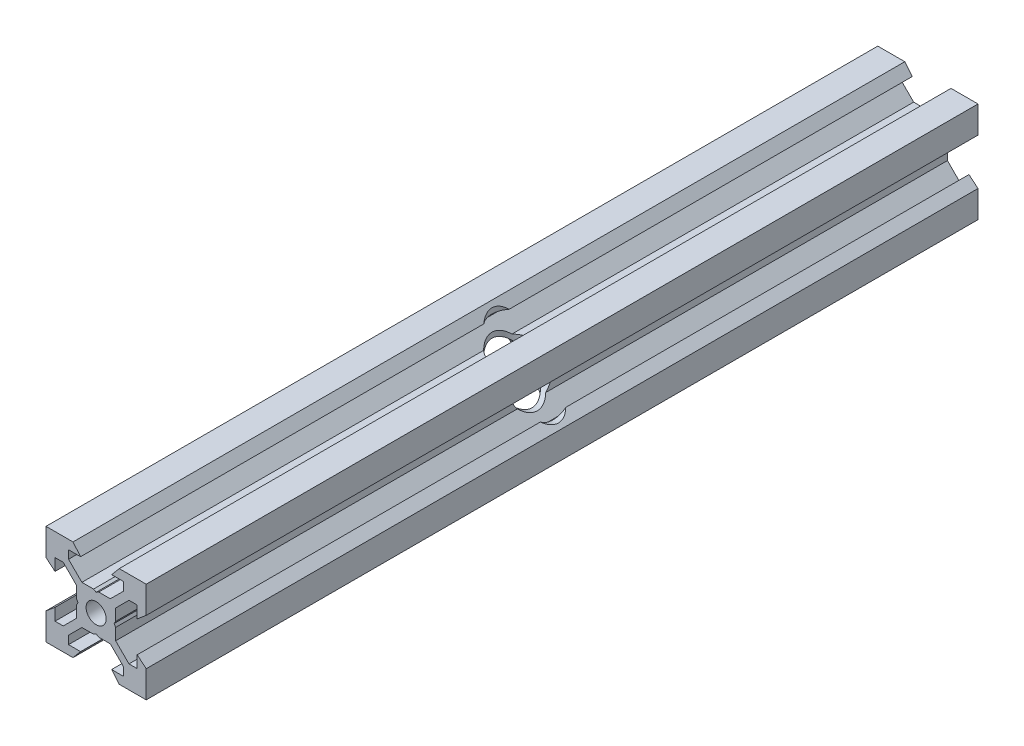
SolidWorks part; units mm, degrees
material "3.3535 (EN-AW 5754)"
ref_plane "Front Plane" through (0, 0, 0) normal (0, 0, 1) x (1, 0, 0)
ref_plane "Top Plane" through (0, 0, 0) normal (0, 1, 0) x (1, 0, 0)
ref_plane "Right Plane" through (0, 0, 0) normal (1, 0, 0) x (0, 0, -1)
sketch "Sketch1" plane through (0, 0, 0) normal (0, 0, 1) x (1, 0, 0)
  line L0 (10, 10) -> (4.6104, 10) construction
  line L1 (10, 10) -> (10, 4.6104) construction
  line L2 (10, -10) -> (10, -4.6104) construction
  line L3 (10, -10) -> (4.6104, -10) construction
  line L4 (10, 10) -> (10, 4.6104)
  line L5 (6.5607, 5.5) -> (8.2, 5.5)
  line L6 (5.5, 8.2) -> (5.5, 6.5607)
  line L7 (10, 10) -> (4.6104, 10)
  line L8 (10, 10) -> (10, 4.6104)
  line L9 (6.5607, 5.5) -> (3.9, 2.8393)
  line L10 (5.5, 6.5607) -> (2.8393, 3.9)
  line L11 (10, 4.6104) -> (8.2, 3.1)
  line L12 (4.6104, 10) -> (3.1, 8.2)
  line L13 (8.2, 3.1) -> (8.2, 5.5)
  line L14 (3.1, 8.2) -> (5.5, 8.2)
  line L15 (-6.5607, 5.5) -> (-8.2, 5.5)
  line L16 (6.5607, -5.5) -> (8.2, -5.5)
  line L17 (3.1, -8.2) -> (5.5, -8.2)
  line L18 (8.2, -3.1) -> (8.2, -5.5)
  line L19 (4.6104, -10) -> (3.1, -8.2)
  line L20 (10, -4.6104) -> (8.2, -3.1)
  line L21 (0.5196, -3.9) -> (0, -3.6)
  line L22 (0.5196, 3.9) -> (0, 3.6)
  line L23 (3.6, 0) -> (3.9, -0.5196)
  line L24 (3.9, 0.5196) -> (3.6, 0)
  line L25 (3.9, 0.5196) -> (3.9, 2.8393)
  line L26 (2.8393, 3.9) -> (0.5196, 3.9)
  line L27 (3.9, -2.8393) -> (3.9, -0.5196)
  line L28 (2.8393, -3.9) -> (0.5196, -3.9)
  line L29 (5.5, -6.5607) -> (2.8393, -3.9)
  line L30 (6.5607, -5.5) -> (3.9, -2.8393)
  line L31 (10, -10) -> (10, -4.6104)
  line L32 (10, -10) -> (4.6104, -10)
  line L33 (5.5, -8.2) -> (5.5, -6.5607)
  line L34 (-6.5607, -5.5) -> (-8.2, -5.5)
  line L35 (10, -10) -> (10, -4.6104)
  line L36 (0, 0) -> (0, 8.2) construction
  line L37 (-10, -10) -> (-4.6104, -10) construction
  line L38 (-10, -10) -> (-10, -4.6104) construction
  line L39 (-10, 10) -> (-10, 4.6104) construction
  line L40 (-10, 10) -> (-4.6104, 10) construction
  line L41 (-10, -10) -> (-10, -4.6104)
  line L43 (-5.5, -8.2) -> (-5.5, -6.5607)
  line L44 (-10, -10) -> (-4.6104, -10)
  line L45 (-10, -10) -> (-10, -4.6104)
  line L46 (-6.5607, -5.5) -> (-3.9, -2.8393)
  line L47 (-5.5, -6.5607) -> (-2.8393, -3.9)
  line L48 (-2.8393, -3.9) -> (-0.5196, -3.9)
  line L49 (-3.9, -2.8393) -> (-3.9, -0.5196)
  line L50 (-2.8393, 3.9) -> (-0.5196, 3.9)
  line L51 (-3.9, 0.5196) -> (-3.9, 2.8393)
  line L52 (-3.9, 0.5196) -> (-3.6, 0)
  line L53 (-3.6, 0) -> (-3.9, -0.5196)
  line L54 (-0.5196, 3.9) -> (0, 3.6)
  line L55 (-0.5196, -3.9) -> (0, -3.6)
  line L56 (-10, -4.6104) -> (-8.2, -3.1)
  line L57 (-4.6104, -10) -> (-3.1, -8.2)
  line L58 (-8.2, -3.1) -> (-8.2, -5.5)
  line L59 (-3.1, -8.2) -> (-5.5, -8.2)
  line L60 (-10, -10) -> (10, -10) construction
  line L61 (-10, -10) -> (-10, 10) construction
  line L62 (-3.1, 8.2) -> (-5.5, 8.2)
  line L63 (-8.2, 3.1) -> (-8.2, 5.5)
  line L64 (-4.6104, 10) -> (-3.1, 8.2)
  line L65 (-10, 4.6104) -> (-8.2, 3.1)
  line L66 (-5.5, 6.5607) -> (-2.8393, 3.9)
  line L67 (-6.5607, 5.5) -> (-3.9, 2.8393)
  line L68 (-10, 10) -> (-10, 4.6104)
  line L69 (-10, 10) -> (-4.6104, 10)
  line L70 (-5.5, 8.2) -> (-5.5, 6.5607)
  line L71 (-10, 10) -> (10, 10) construction
  line L72 (-10, 10) -> (-10, 4.6104)
  line L73 (10, -10) -> (10, 10) construction
  line L74 (-10, -10) -> (10, 10) construction
  line L75 (-10, 10) -> (10, -10) construction
  circle A0 centre (0, 0) radius 2
  dimension "D7" = 4
  dimension "D1" = 20
  dimension "D2" = 5.3896
  dimension "D3" = 4.5
  dimension "D4" = 50
  dimension "D5" = 1.8
  dimension "D6" = 1.5104
  dimension "D8" = 5.5
  dimension "D9" = 120
  dimension "D10" = 0.3
  dimension "D11" = 2.3197
  dimension "D12" = 7.8
  dimension "D13" = 7.8
  dimension "D14" = 1.5
  dimension "D15" = 2.6607
extrude "Boss-Extrude1" add sketch "Sketch1" along normal blind 166 contours L70 L62 L64 L69 L68 L65 L63 L15 L67 L51 L52 L53 L49 L46 L34 L58 L56 L41 L44 L57 L59 L43 L47 L48 L55 L21 L28 L29 L33 L17 L19 L32 L31 L20 L18 L16 L30 L27 L23 L24 L25 L9 L5 L13 L11 L4 L7 L12 L14 L6 L10
sketch "Sketch4" plane through (0, 0, 0) normal (1, 0, 0) x (0, 0, -1)
  line L0 (-166, 0) -> (0, 0) construction
  circle A0 centre (-83, 0) radius 4
  dimension "D1" = 8
extrude "Cut-Extrude1" cut sketch "Sketch4" against normal through all both and the other way through all
sketch "Sketch5" plane through (0, 0, 0) normal (0, 1, 0) x (1, 0, 0)
  line L0 (0, 0) -> (0, -166) construction
  circle A0 centre (0, -83) radius 4
  dimension "D1" = 8
extrude "Cut-Extrude2" cut sketch "Sketch5" against normal through all both and the other way through all
